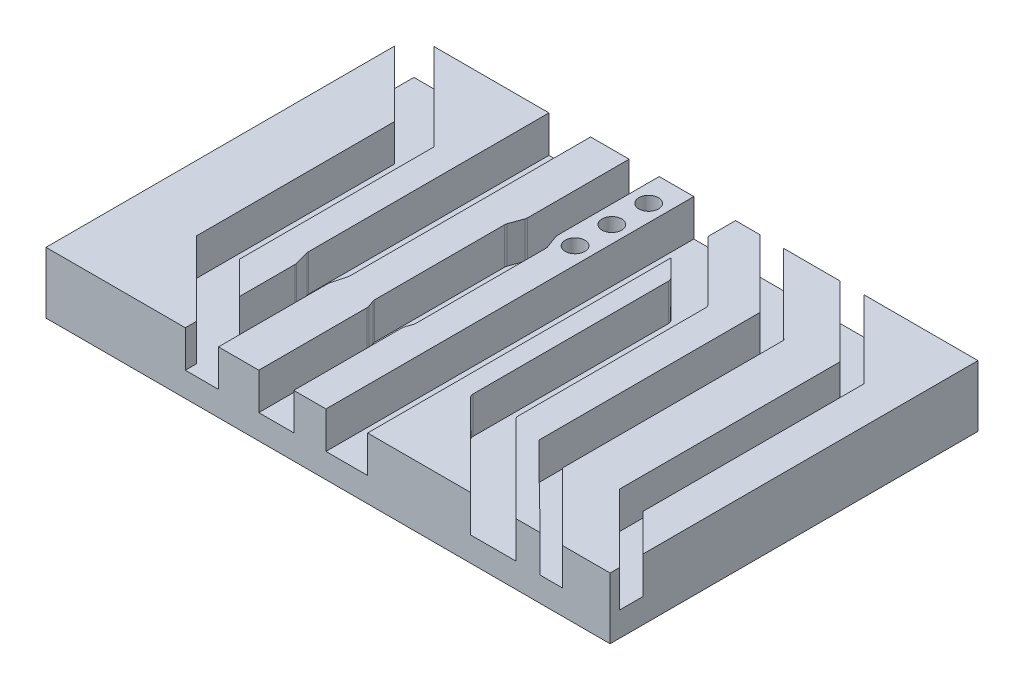
SolidWorks part; units mm, degrees
material "RED BOARD (PP-1052)"
ref_plane "Z" through (0, 0, 0) normal (0, 0, 1) x (1, 0, 0)
ref_plane "Y" through (0, 0, 0) normal (0, 1, 0) x (1, 0, 0)
ref_plane "X" through (0, 0, 0) normal (1, 0, 0) x (0, 0, -1)
sketch "Sketch1" plane through (0, 0, 0) normal (0, 1, 0) x (1, 0, 0)
  line L1 (-146.05, 95.25) -> (146.05, 95.25)
  line L2 (-146.05, 95.25) -> (-146.05, -95.25)
  line L3 (-146.05, -95.25) -> (146.05, -95.25)
  line L4 (146.05, 95.25) -> (146.05, -95.25)
  point P4 (0, 95.25)
  point P5 (-146.05, 0)
  point P6 (0, 0)
  dimension "D1" = 190.5
  dimension "D2" = 292.1
extrude "Boss-Extrude1" add sketch "Sketch1" along normal blind 31.75
sketch "Sketch2" plane through (0, 0, 0) normal (0, 1, 0) x (1, 0, 0)
  line L0 (-146.05, 2.286) -> (146.05, 2.286) construction
  line L1 (-146.05, 95.25) -> (-146.05, -95.25) construction
  line L2 (146.05, 95.25) -> (146.05, -95.25) construction
  line L3 (-17.4625, 0) -> (17.4625, 0) construction
  text T0 "2103-136"
  dimension "D1" = 2.286
extrude "Job+Det#" [suppressed] cut sketch "Sketch2" along normal blind 0.0508
sketch "Sketch5" plane through (0, 31.75, 0) normal (0, 1, 0) x (1, 0, 0)
  line L0 (-54.538, 56.6459) -> (-54.538, 45.2826)
  line L1 (-35.8696, -54.7687) -> (-35.8696, -113.2563)
  line L2 (-17.7396, -54.7687) -> (-17.7396, -42.0687)
  line L3 (-17.7396, -54.7687) -> (-17.7396, -38.5465)
  line L4 (-76.1158, -9.143) -> (-76.1158, 45.2826)
  line L5 (-54.538, -9.143) -> (-54.538, 45.2826)
  line L6 (-54.538, -9.143) -> (-54.538, 45.2826)
  line L7 (-54.538, -9.143) -> (-54.538, -29.7278)
  line L8 (-35.8696, -113.2563) -> (-17.7396, -113.2563)
  line L9 (-73.9024, -37.9883) -> (-73.9024, -113.2563)
  line L10 (-76.1158, -9.143) -> (-76.1158, 45.2826)
  line L11 (-76.1158, -11.9309) -> (-76.1158, -9.143)
  line L12 (-76.1158, -29.3934) -> (-76.1158, -11.9309)
  line L13 (-76.1158, -29.7278) -> (-76.1158, -11.9309)
  line L14 (-76.1158, 45.2826) -> (-76.1158, 56.6459)
  line L15 (-76.1158, 123.9385) -> (-54.538, 123.9385)
  line L16 (-54.538, 123.9385) -> (-54.538, 64.9009)
  line L17 (-17.7396, -113.2563) -> (-17.7396, -54.7687)
  line L18 (-76.0292, -30.0508) -> (-73.9024, -37.9883)
  line L19 (-56.7514, -37.9883) -> (-54.6245, -30.0508)
  line L20 (-56.7514, -37.9883) -> (-54.538, -29.7278)
  line L21 (-76.1158, -29.7278) -> (-73.9024, -37.9883)
  line L22 (-73.9024, -113.2563) -> (-56.7514, -113.2563)
  line L23 (-56.7514, -113.2563) -> (-56.7514, -37.9883)
  line L24 (-76.1158, 64.9009) -> (-76.1158, 123.9385)
  line L26 (-37.4404, -34.231) -> (-34.2715, -42.9375)
  line L27 (-37.4404, -34.231) -> (-35.8696, -38.5465)
  line L28 (-19.3378, -42.9375) -> (-16.1689, -34.231)
  line L29 (-35.8696, -42.0687) -> (-35.8696, -54.7687)
  line L30 (-35.8696, -38.5465) -> (-35.8696, -54.7687)
  line L31 (-17.7396, -38.5465) -> (-16.1689, -34.231)
  line L33 (-34.5946, 54.7687) -> (-34.5946, 42.0687)
  line L34 (-34.5946, 54.7687) -> (-34.5946, 42.0495)
  line L35 (-54.538, 56.6459) -> (-54.538, 64.9009)
  line L36 (-19.0146, 42.0687) -> (-19.0146, 54.7687)
  line L37 (-19.0146, 42.0495) -> (-19.0146, 54.7687)
  line L39 (-34.2715, 42.9375) -> (-37.4404, 34.231)
  line L40 (-34.5946, 42.0495) -> (-37.4404, 34.231)
  line L41 (-37.4404, 34.231) -> (-37.4404, -34.231)
  line L42 (-16.1689, 34.231) -> (-19.3378, 42.9375)
  line L43 (-16.1689, 34.231) -> (-19.0146, 42.0495)
  line L44 (-16.1689, -34.231) -> (-16.1689, 34.231)
  line L45 (-34.5946, 54.7687) -> (-34.5946, 123.9385)
  line L46 (-34.5946, 123.9385) -> (-19.0146, 123.9385)
  line L47 (-19.0146, 123.9385) -> (-19.0146, 54.7687)
  line L53 (68.0071, -12.827) -> (68.0071, -53.936)
  line L56 (20.49, 80.981) -> (20.49, 107.7878)
  line L59 (75.7332, -61.6621) -> (68.0071, -53.936)
  line L62 (20.49, -17.0559) -> (20.49, 37.3697)
  line L65 (20.49, 37.3697) -> (20.49, 61.776)
  line L77 (-76.1158, 56.6459) -> (-76.1158, 64.9009)
  line L78 (69.1643, 71.3973) -> (30.2796, 110.282)
  line L79 (-1.0878, -17.0559) -> (-1.0878, 37.3697)
  line L82 (63.0691, 65.302) -> (72.8043, 55.5668)
  line L84 (20.49, 107.7878) -> (-1.0878, 107.7878)
  line L85 (63.0691, 65.302) -> (68.0071, 60.364)
  line L87 (-1.0878, 107.7878) -> (-1.0878, 37.3697)
  line L92 (63.0691, 65.302) -> (23.6877, 104.6834)
  line L94 (20.49, -17.0559) -> (20.49, -113.2563)
  line L95 (78.8995, 61.6621) -> (69.1643, 71.3973)
  line L98 (78.8995, 61.6621) -> (69.1643, 71.3973)
  line L101 (23.6877, 104.6834) -> (30.2796, 110.282)
  line L103 (20.49, -113.2563) -> (-1.0878, -113.2563)
  line L104 (-1.0878, -113.2563) -> (-1.0878, -17.0559)
  line L105 (68.0071, 12.827) -> (68.0071, -12.827)
  line L106 (68.0071, 12.827) -> (68.0071, -12.827)
  line L107 (85.827, -71.7559) -> (120.9116, -106.0608)
  line L108 (86.6256, 12.827) -> (86.6256, -12.827)
  line L109 (86.6256, 12.827) -> (86.6256, -12.827)
  line L110 (91.9222, -65.6606) -> (128.7941, -102.5325)
  line L111 (75.7332, -61.6621) -> (85.827, -71.7559)
  line L112 (75.7332, -61.6621) -> (85.827, -71.7559)
  line L113 (86.6256, -12.827) -> (86.6256, -60.364)
  line L114 (91.9222, -65.6606) -> (81.8284, -55.5668)
  line L116 (91.9222, -65.6606) -> (86.6256, -60.364)
  line L117 (86.6256, 12.827) -> (86.6256, 54.1077)
  line L118 (30.2796, -19.2405) -> (30.2796, 19.2405)
  line L119 (30.2796, -51.7349) -> (30.2796, 51.9864)
  line L120 (78.8995, 61.6621) -> (86.6256, 54.1077)
  line L121 (51.8574, -19.2405) -> (51.8574, 19.2405)
  line L122 (51.8574, -49.8651) -> (51.8574, 49.6136)
  line L123 (68.0071, 12.827) -> (68.0071, 60.364)
  line L124 (13.8166, 68.4494) -> (33.3383, 48.9277)
  line L125 (20.49, 61.776) -> (30.2796, 51.9864)
  line L126 (128.7941, -102.5325) -> (120.9116, -106.0608)
  line L127 (42.9408, 58.5302) -> (23.4191, 78.0519)
  line L128 (51.8574, 49.6136) -> (20.49, 80.981)
  line L130 (38.1355, -59.5908) -> (57.6572, -79.1126)
  line L131 (30.2796, -51.7349) -> (111.8422, -133.2975)
  line L132 (111.8422, -133.2975) -> (131.6119, -129.6196)
  line L133 (69.3811, -67.3887) -> (49.8594, -47.867)
  line L134 (131.6119, -129.6196) -> (51.8574, -49.8651)
  dimension "D3" = 2.54
  dimension "D4" = 2.54
  dimension "D6" = 2.54
  dimension "D9" = 2.54
  dimension "D14" = 3.81
  dimension "D26" = 2.54
  dimension "D16" = 3.81
  dimension "D1" = 2.54
  dimension "D2" = 2.54
  dimension "D5" = 2.54
  dimension "D7" = 2.54
  dimension "D8" = 2.54
  dimension "D10" = 2.54
  dimension "D11" = 2.54
  dimension "D12" = 2.54
  dimension "D13" = 2.54
  dimension "D15" = 3.81
  dimension "D17" = 3.81
  dimension "D18" = 3.81
  dimension "D19" = 3.81
  dimension "D27" = 2.54
  dimension "D28" = 2.54
  dimension "D29" = 2.54
  dimension "D30" = 2.54
  dimension "D31" = 2.54
extrude "Cut-Extrude1" cut sketch "Sketch5" against normal up to vertex (19.05 mm away)
fillet "Fillet1" radius 3.175 16 edges at (51.8574, 22.225, 49.8651) (30.2796, 22.225, 51.7349) (51.8574, 22.225, -49.6136) (30.2796, 22.225, -51.9864) (-17.7396, 22.225, 38.5465) (-16.1689, 22.225, 34.231) (-37.4404, 22.225, 34.231) (-35.8696, 22.225, 38.5465) (-16.1689, 22.225, -34.231) (-19.0146, 22.225, -42.0495) (-34.5946, 22.225, -42.0495) (-37.4404, 22.225, -34.231) (-54.538, 22.225, 29.7278) (-56.7514, 22.225, 37.9883) (-76.1158, 22.225, 29.7278) (-73.9024, 22.225, 37.9883)
sketch "Sketch8" plane through (0, 31.75, 0) normal (0, 1, 0) x (1, 0, 0)
  line L0 (-9.7513, 42.4122) -> (-9.7513, 61.4622) construction
  line L1 (-9.7513, 61.4622) -> (-9.7513, 80.5122) construction
  circle A0 centre (-9.7513, 42.4122) radius 5.08
  circle A1 centre (-9.7513, 61.4622) radius 5.08
  circle A2 centre (-9.7513, 80.5122) radius 5.08
  dimension "D1" = 10.16
  dimension "D4" = 10.16
  dimension "D5" = 10.16
  dimension "D2" = 19.05
  dimension "D3" = 19.05
extrude "Cut-Extrude2" cut sketch "Sketch8" against normal blind 12.7
sketch "Sketch9" plane through (0, 31.75, 0) normal (0, 1, 0) x (1, 0, 0)
  line L0 (-9.7513, 42.4122) -> (-9.7513, 27.8767) construction
sketch "Sketch10" plane through (0, 31.75, 0) normal (0, 1, 0) x (1, 0, 0)
  line L2 (110.862, 12.827) -> (110.862, -12.827)
  line L3 (110.862, 12.827) -> (110.862, -12.827)
  line L5 (126.9405, 12.827) -> (126.9405, -12.827)
  line L6 (126.9405, 12.827) -> (126.9405, -12.827)
  line L8 (133.6872, -65.8407) -> (123.4133, -55.5668)
  line L9 (133.6872, -65.8407) -> (126.9405, -59.094)
  line L11 (117.3181, -61.6621) -> (127.5919, -71.936)
  line L12 (117.3181, -61.6621) -> (127.5919, -71.936)
  line L21 (104.8327, 65.1233) -> (114.3891, 55.5668)
  line L22 (104.8327, 65.1233) -> (110.862, 59.094)
  line L23 (133.6872, -65.8407) -> (167.3754, -99.5289)
  line L24 (120.4844, 61.6621) -> (110.928, 71.2185)
  line L25 (120.4844, 61.6621) -> (110.928, 71.2185)
  line L26 (127.5919, -71.936) -> (167.3754, -111.7194)
  line L27 (167.3754, -111.7194) -> (167.3754, -99.5289)
  line L28 (110.862, 12.827) -> (110.862, 59.094)
  line L29 (126.9405, 12.827) -> (126.9405, 55.206)
  line L30 (120.4844, 61.6621) -> (126.9405, 55.206)
  line L31 (126.9405, -12.827) -> (126.9405, -59.094)
  line L32 (110.862, -12.827) -> (110.862, -55.206)
  line L33 (117.3181, -61.6621) -> (110.862, -55.206)
  line L34 (104.8327, 65.1233) -> (59.1251, 110.8309)
  line L35 (110.928, 71.2185) -> (71.3156, 110.8309)
  line L36 (71.3156, 110.8309) -> (59.1251, 110.8309)
  dimension "D1" = 2.54
  dimension "D2" = 2.54
  dimension "D3" = 3.81
  dimension "D4" = 3.81
  dimension "D5" = 3.81
  dimension "D6" = 3.81
extrude "Cut-Extrude3" cut sketch "Sketch10" against normal up to vertex (19.05 mm away) up to point (109.8551, 12.7, 95.25)
ref_plane "Plane1" through (-97.3006, 26.9875, -35.4385) normal (0, 0, -1) x (-1, 0, 0)
sketch "Sketch13" plane through (0, 31.75, 0) normal (0, 1, 0) x (1, 0, 0)
  line L2 (-90.6362, -19.2405) -> (-90.6362, 19.2405)
  line L3 (-90.6362, -19.2405) -> (-90.6362, 19.2405)
  line L5 (-112.2139, -19.2405) -> (-112.2139, 19.2405)
  line L6 (-112.2139, -19.2405) -> (-112.2139, 19.2405)
  line L8 (-103.858, -59.3837) -> (-84.4828, -78.759)
  line L9 (-103.858, -59.3837) -> (-84.4828, -78.759)
  line L11 (-73.4661, -67.7423) -> (-92.8413, -48.367)
  line L12 (-73.4661, -67.7423) -> (-90.6362, -50.5722)
  line L14 (-129.0305, 68.0958) -> (-109.6552, 48.7206)
  line L15 (-129.0305, 68.0958) -> (-112.2139, 51.2793)
  line L16 (-99.3456, 59.0302) -> (-90.6362, 50.3207)
  line L17 (-99.3456, 59.0302) -> (-118.7209, 78.4054)
  line L18 (-99.3456, 59.0302) -> (-118.7209, 78.4054)
  line L19 (-90.6362, 19.2405) -> (-90.6362, 50.3207)
  line L20 (-112.2139, 19.2405) -> (-112.2139, 51.2793)
  line L21 (-112.2139, -19.2405) -> (-112.2139, -51.0278)
  line L22 (-103.858, -59.3837) -> (-112.2139, -51.0278)
  line L23 (-90.6362, -19.2405) -> (-90.6362, -50.5722)
  line L24 (-84.4828, -78.759) -> (-70.5832, -92.6586)
  line L25 (-70.5832, -92.6586) -> (-70.5832, -70.6251)
  line L26 (-73.4661, -67.7423) -> (-70.5832, -70.6251)
  line L27 (-129.0305, 68.0958) -> (-162.6131, 101.6784)
  line L28 (-118.7209, 78.4054) -> (-162.6131, 122.2976)
  line L29 (-162.6131, 122.2976) -> (-162.6131, 101.6784)
  dimension "D1" = 2.54
  dimension "D2" = 2.54
  dimension "D3" = 2.54
  dimension "D4" = 2.54
  dimension "D5" = 2.54
  dimension "D6" = 2.54
extrude "Cut-Extrude4" cut sketch "Sketch13" against normal up to vertex
